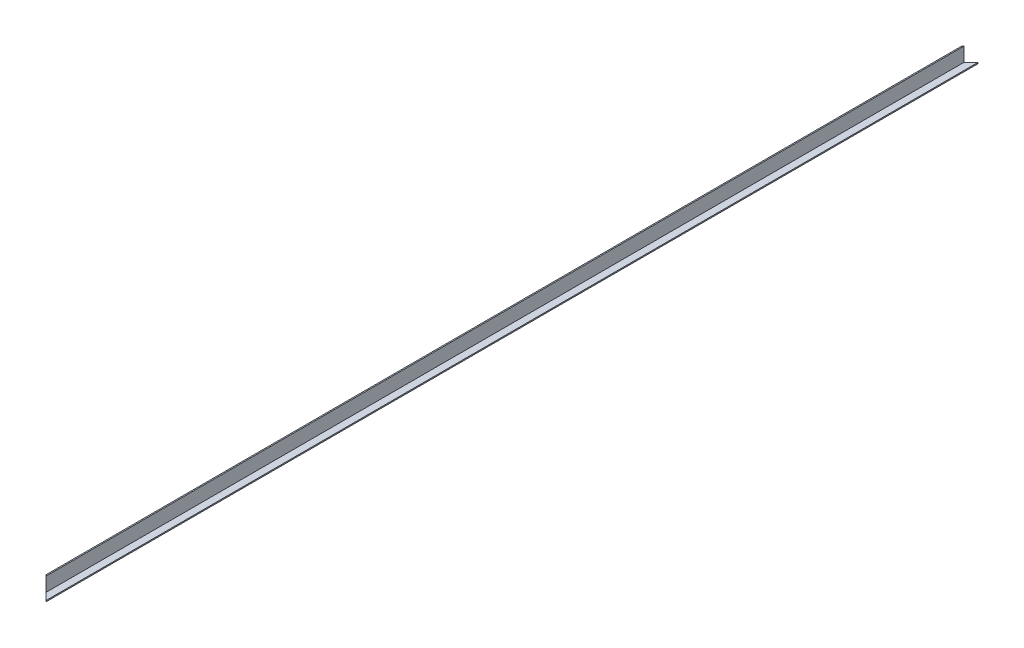
SolidWorks part; units mm, degrees
ref_plane "Front Plane" through (0, 0, 0) normal (0, 0, 1) x (1, 0, 0)
ref_plane "Top Plane" through (0, 0, 0) normal (0, 1, 0) x (1, 0, 0)
ref_plane "Right Plane" through (0, 0, 0) normal (1, 0, 0) x (0, 0, -1)
sketch "Sketch1" plane through (0, 0, 0) normal (0, 0, 1) x (1, 0, 0)
  line L0 (-9.75, -9.75) -> (9.75, -9.75)
  line L1 (-9.75, 9.75) -> (9.75, 9.75) construction
  line L2 (-9.75, 9.75) -> (-9.75, -9.75) construction
  line L3 (-9.75, -9.75) -> (9.75, -9.75) construction
  line L4 (9.75, 9.75) -> (9.75, -9.75) construction
  line L5 (-9.75, 9.75) -> (9.75, -9.75) construction
  line L6 (-9.75, -9.75) -> (9.75, 9.75) construction
  line L7 (0, 9.75) -> (0, -9.75) construction
  line L8 (-9.75, -8.25) -> (-0.75, -8.25)
  line L9 (-0.75, 9.75) -> (-0.75, -8.25)
  line L10 (0.75, 9.75) -> (0.75, -8.25)
  line L11 (-0.75, 9.75) -> (0.75, 9.75)
  line L12 (9.75, -8.25) -> (9.75, -9.75)
  line L13 (-9.75, -8.25) -> (-9.75, -9.75)
  line L14 (-0.75, 9.75) -> (-0.75, -9.75) construction
  line L15 (0.75, -8.25) -> (9.75, -8.25)
  line L16 (-9.75, -8.25) -> (9.75, -8.25) construction
  line L17 (0.75, 9.75) -> (0.75, -9.75) construction
  point P0 (0, 0)
  dimension "D1" = 19.5
  dimension "D2" = 19.5
  dimension "D3" = 1.5
  dimension "D4" = 0.75
  dimension "D5" = 0.75
extrude "Boss-Extrude1" add sketch "Sketch1" along normal blind 1190
sketch "Sketch2" plane through (0, -8.25, 0) normal (0, 1, 0) x (1, 0, 0)
  line L0 (9.75, 0) -> (-9.75, -19.5)
  line L1 (-9.75, -1190) -> (-9.75, 0) construction
  line L2 (9.75, 0) -> (0.75, 0) construction
  line L3 (9.75, -1190) -> (-9.75, -1170.5)
  line L4 (9.75, -1190) -> (0.75, -1190) construction
  line L5 (-9.75, -1170.5) -> (-13.5009, -1170.5)
  line L6 (-13.5009, -1170.5) -> (-13.5009, -1195.414)
  line L7 (-13.5009, -1195.414) -> (9.75, -1195.414)
  line L8 (9.75, -1195.414) -> (9.75, -1190)
  line L9 (9.75, 0) -> (9.75, 8.4407)
  line L10 (9.75, 8.4407) -> (-15.8745, 8.4407)
  line L11 (-15.8745, 8.4407) -> (-15.8745, -19.5)
  line L12 (-15.8745, -19.5) -> (-9.75, -19.5)
  dimension "D1" = 45
  dimension "D2" = 45
extrude "Cut-Extrude1" cut sketch "Sketch2" against normal through all and the other way through all
